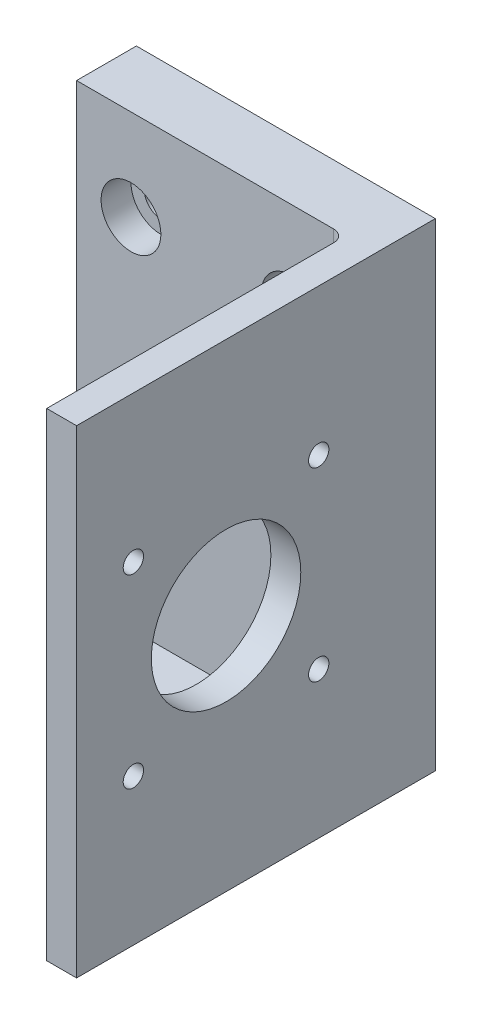
SolidWorks part; units mm, degrees
ref_plane "Front Plane" through (0, 0, 0) normal (0, 0, 1) x (1, 0, 0)
ref_plane "Top Plane" through (0, 0, 0) normal (0, 1, 0) x (1, 0, 0)
ref_plane "Right Plane" through (0, 0, 0) normal (1, 0, 0) x (0, 0, -1)
sketch "Sketch1" plane through (0, 0, 0) normal (0, 0, 1) x (1, 0, 0)
  line L1 (25, -40) -> (-25, -40)
  line L2 (25, -40) -> (25, 40)
  line L3 (25, 40) -> (-25, 40)
  line L4 (-25, -40) -> (-25, 40)
  line L5 (25, -40) -> (-25, 40) construction
  line L6 (25, 40) -> (-25, -40) construction
  point P0 (0, 0)
  dimension "D1" = 50
  dimension "D2" = 80
extrude "Boss-Extrude1" add sketch "Sketch1" along normal blind 10
sketch "Sketch2" plane through (0, 0, 10) normal (0, 0, 1) x (1, 0, 0)
  line L0 (-25, -40) -> (25, -40) construction
  line L1 (25, 40) -> (20, 40)
  line L2 (25, 40) -> (25, -40)
  line L3 (25, -40) -> (20, -40)
  line L4 (20, 40) -> (20, -40)
  dimension "D1" = 5
extrude "Boss-Extrude2" add sketch "Sketch2" along normal blind 50
sketch "Sketch3" plane through (25, 0, 0) normal (1, 0, 0) x (0, 0, -1)
  line L0 (-60, -40) -> (-60, 40) construction
  line L3 (-60, 0) -> (0, 0) construction
  line L4 (-60, -40) -> (-60, 40) construction
  line L5 (-10, 40) -> (-10, -40) construction
  line L6 (-10, 40) -> (-10, -40) construction
  line L7 (-60, 40) -> (-10, 40) construction
  line L8 (-60, -40) -> (-10, -40) construction
  line L9 (-35, -40) -> (-35, 40) construction
  circle A0 centre (-35, 0) radius 12.5
  dimension "D1" = 25
extrude "Cut-Extrude1" cut sketch "Sketch3" against normal through all
hole_wizard "M3 Clearance Hole1" positions "Sketch4" profile "Sketch5" hole size "M3" standard "ANSI Metric" end condition through all
sketch "Sketch4" plane through (25, 0, 0) normal (1, 0, 0) x (0, 0, -1)
  line L8 (-19.5, -15.5) -> (-50.5, -15.5) construction
  line L9 (-19.5, -15.5) -> (-19.5, 15.5) construction
  line L10 (-19.5, 15.5) -> (-50.5, 15.5) construction
  line L11 (-50.5, -15.5) -> (-50.5, 15.5) construction
  line L12 (-19.5, -15.5) -> (-50.5, 15.5) construction
  line L13 (-19.5, 15.5) -> (-50.5, -15.5) construction
  circle A0 centre (-35, 0) radius 12.5 construction
  circle A1 centre (-35, 0) radius 12.5 construction
  point P17 (-35, 0)
  point P18 (-50.5, 15.5)
  point P187 (-19.5, -15.5)
  point P188 (-19.5, 15.5)
  point P189 (-50.5, -15.5)
  dimension "D1" = 31
  dimension "D2" = 31
sketch "Sketch5" plane through (25, -15.5, 50.5) normal (0, 1, 0) x (0, 0, -1)
  line L0 (0, 0) -> (0, 50)
  line L1 (0, 50) -> (1.7, 50)
  line L2 (1.7, 50) -> (1.7, 0)
  line L5 (1.7, 0) -> (0, 0)
  line L11 (0, -6.35) -> (0, 107.95) construction
  dimension "Thru Hole Dia." = 3.4
  dimension "Thru Hole Depth" = 50
hole_wizard "CBORE for M5 SHCS1" positions "Sketch6" profile "Sketch7" counterbore size "M5" standard "ANSI Metric" end condition through all
sketch "Sketch6" plane through (0, 0, 10) normal (0, 0, 1) x (1, 0, 0)
  line L0 (-2.5, 40) -> (-2.5, -40) construction
  line L1 (20, 40) -> (-25, 40) construction
  line L2 (-25, -40) -> (20, -40) construction
  line L4 (-25, 0) -> (20, 0) construction
  line L5 (-25, 40) -> (-25, -40) construction
  line L6 (20, 40) -> (20, -40) construction
  point P0 (-15.9029, 24.76)
  point P2 (10.9029, 24.76)
  point P4 (-15.9029, -24.76)
  point P28 (10.9029, -24.76)
  point P33 (-15.9029, 24.76)
  dimension "D1" = 15.24
  dimension "D2" = 15.24
sketch "Sketch7" plane through (-15.9029, 24.76, 10) normal (1, 0, 0) x (0, -1, 0)
  line L0 (0, 0) -> (0, 10)
  line L1 (0, 10) -> (2.75, 10)
  line L3 (2.75, 10) -> (2.75, 5)
  line L4 (2.75, 5) -> (5, 5)
  line L5 (5, 5) -> (5, 0)
  line L7 (5, 0) -> (0, 0)
  line L11 (0, -6.35) -> (0, 107.95) construction
  dimension "Thru Hole Dia." = 5.5
  dimension "Thru Hole Depth" = 10
  dimension "C'Bore Dia." = 10
  dimension "C'Bore Depth" = 5
fillet "Fillet11" radius 2 1 edges at (20, 0, 10)
sketch "Sketch8" plane through (0, -40, 0) normal (0, -1, 0) x (1, 0, 0)
  line L0 (20, 60) -> (-25, 10)
  line L1 (-25, 10) -> (20, 10)
  line L2 (20, 60) -> (20, 10)
  point P4 (0, 0)
  point P7 (20.3867, 10)
  point P8 (20.0402, 10)
extrude "Boss-Extrude3" add sketch "Sketch8" against normal blind 5.08
